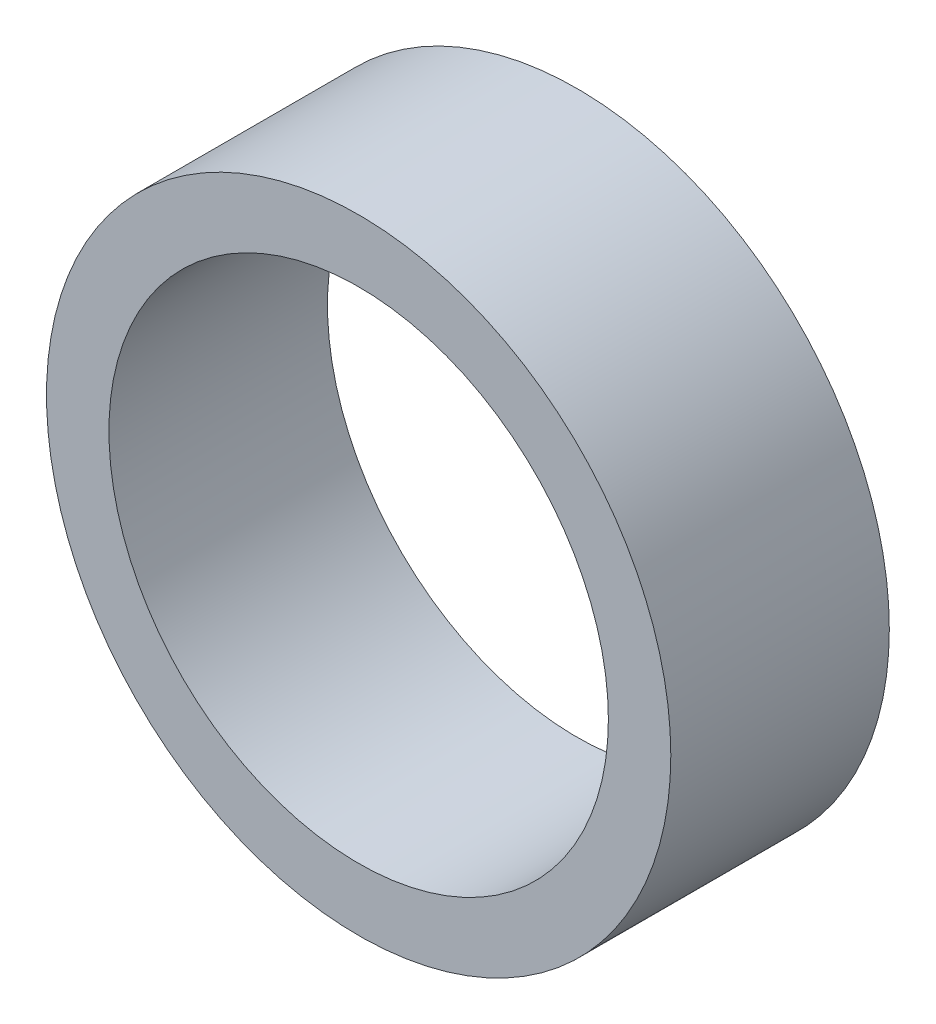
SolidWorks part; units mm, degrees
ref_plane "前视基准面" through (0, 0, 0) normal (0, 0, 1) x (1, 0, 0)
ref_plane "上视基准面" through (0, 0, 0) normal (0, 1, 0) x (1, 0, 0)
ref_plane "右视基准面" through (0, 0, 0) normal (1, 0, 0) x (0, 0, -1)
sketch "草图2" plane through (0, 0, 0) normal (0, 0, 1) x (1, 0, 0)
  circle A0 centre (0, 0) radius 4
  circle A1 centre (0, 0) radius 5
extrude "凸台-拉伸1" add sketch "草图2" along normal blind 3.5
